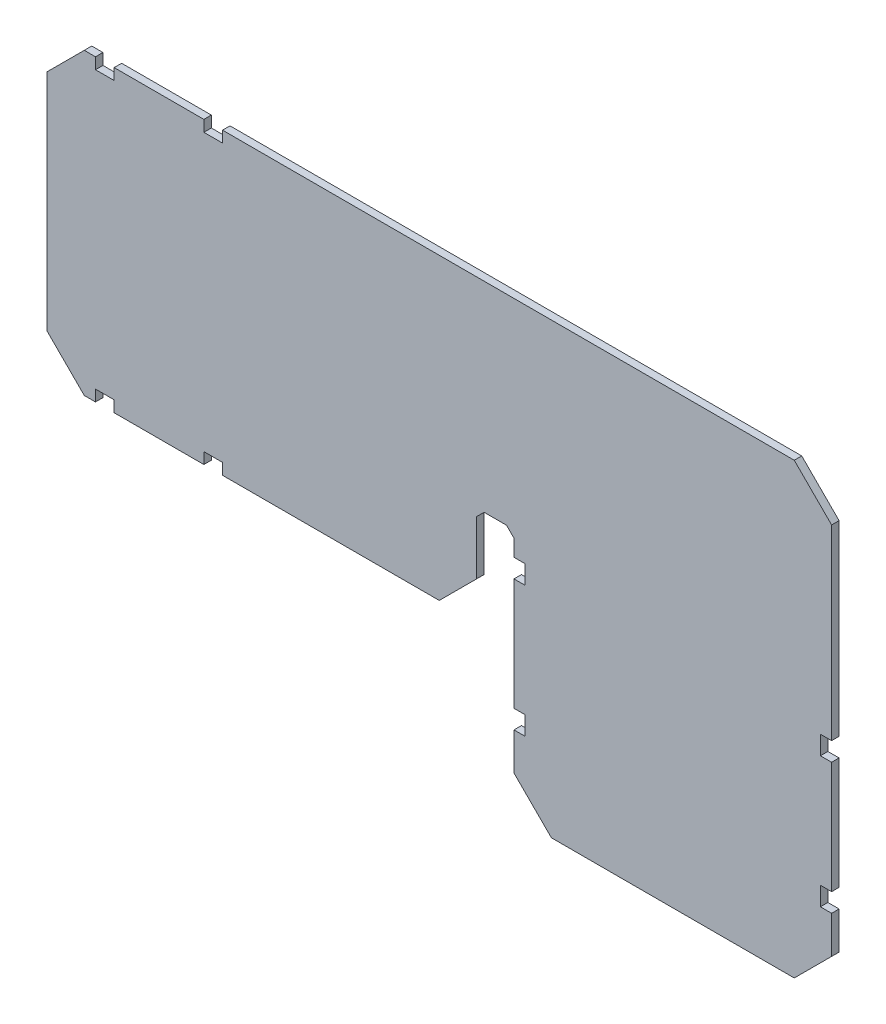
SolidWorks part; units mm, degrees
ref_plane "Front Plane" through (0, 0, 0) normal (0, 0, 1) x (1, 0, 0)
ref_plane "Top Plane" through (0, 0, 0) normal (0, 1, 0) x (1, 0, 0)
ref_plane "Right Plane" through (0, 0, 0) normal (1, 0, 0) x (0, 0, -1)
sketch "Sketch1" plane through (0, 0, 0) normal (0, 0, 1) x (1, 0, 0)
  line L0 (80, 24.4343) -> (82, 26.4343)
  line L1 (-5, 0) -> (7, 0)
  line L2 (-5, 80) -> (-5, 0) construction
  line L3 (-5, 80) -> (7, 80)
  line L4 (175, 0) -> (175, 15)
  line L5 (-5, 0) -> (-5, 80) construction
  line L6 (80, 0) -> (80, 24.4343)
  line L7 (82, 26.4343) -> (88, 26.4343)
  line L8 (90, 0) -> (90, 15)
  line L9 (88, 26.4343) -> (90, 24.4343)
  line L10 (-5, 80) -> (-17, 80)
  line L11 (-22, 80) -> (-35, 80)
  line L12 (175, 0) -> (175, -15)
  line L13 (175, -40) -> (90, -40)
  line L14 (90, 0) -> (90, -15)
  line L15 (-5, 0) -> (-17, 0)
  line L16 (-35, 80) -> (-35, 0)
  line L17 (-35, 40) -> (24.815, 40) construction
  line L18 (-22, 77) -> (-22, 80)
  line L19 (-22, 77) -> (-17, 77)
  line L20 (-17, 80) -> (-17, 77)
  line L21 (-17, 0) -> (-17, 3)
  line L22 (-22, 3) -> (-17, 3)
  line L23 (-22, 3) -> (-22, 0)
  line L24 (12, 3) -> (12, 0)
  line L25 (12, 3) -> (7, 3)
  line L26 (7, 0) -> (7, 3)
  line L27 (7, 80) -> (7, 77)
  line L28 (12, 77) -> (7, 77)
  line L29 (12, 77) -> (12, 80)
  line L30 (12, 0) -> (80, 0)
  line L31 (-22, 0) -> (-35, 0)
  line L32 (12, 80) -> (175, 80)
  line L33 (90, 0) -> (175, 0) construction
  line L34 (90, -15) -> (93, -15)
  line L35 (93, -15) -> (93, -20)
  line L36 (93, -20) -> (90, -20)
  line L37 (132.5, -40) -> (132.5, 28.2751) construction
  line L38 (172, -20) -> (175, -20)
  line L39 (172, -15) -> (172, -20)
  line L40 (175, -15) -> (172, -15)
  line L41 (175, 15) -> (172, 15)
  line L42 (172, 15) -> (172, 20)
  line L43 (172, 20) -> (175, 20)
  line L44 (93, 20) -> (90, 20)
  line L45 (93, 15) -> (93, 20)
  line L46 (90, 15) -> (93, 15)
  line L47 (90, 20) -> (90, 24.4343)
  line L48 (90, -20) -> (90, -40)
  line L49 (175, -20) -> (175, -40)
  line L50 (175, 20) -> (175, 80)
  line L51 (85, 26.4343) -> (85, 102.3368) construction
  point P6 (90, 26.4343)
  point P7 (80, 26.4343)
  dimension "D1" = 180
  dimension "D2" = 80
  dimension "D3" = 90
  dimension "D4" = 10
  dimension "D7" = 2
  dimension "D8" = 2
  dimension "D5" = 40
  dimension "D6" = 120
  dimension "D9" = 15
  dimension "D10" = 12
  dimension "D11" = 5
  dimension "D12" = 5
  dimension "D13" = 3
  dimension "D14" = 3
extrude "Boss-Extrude1" add sketch "Sketch1" along normal blind 2
chamfer "Chamfer1" distance 10 angle 45 5 edges at (175, 80, 1) (175, -40, 1) (90, -40, 1) (-35, 0, 1) (-35, 80, 1)
chamfer "Chamfer2" distance 10 angle 45 1 edges at (80, 0, 1)
